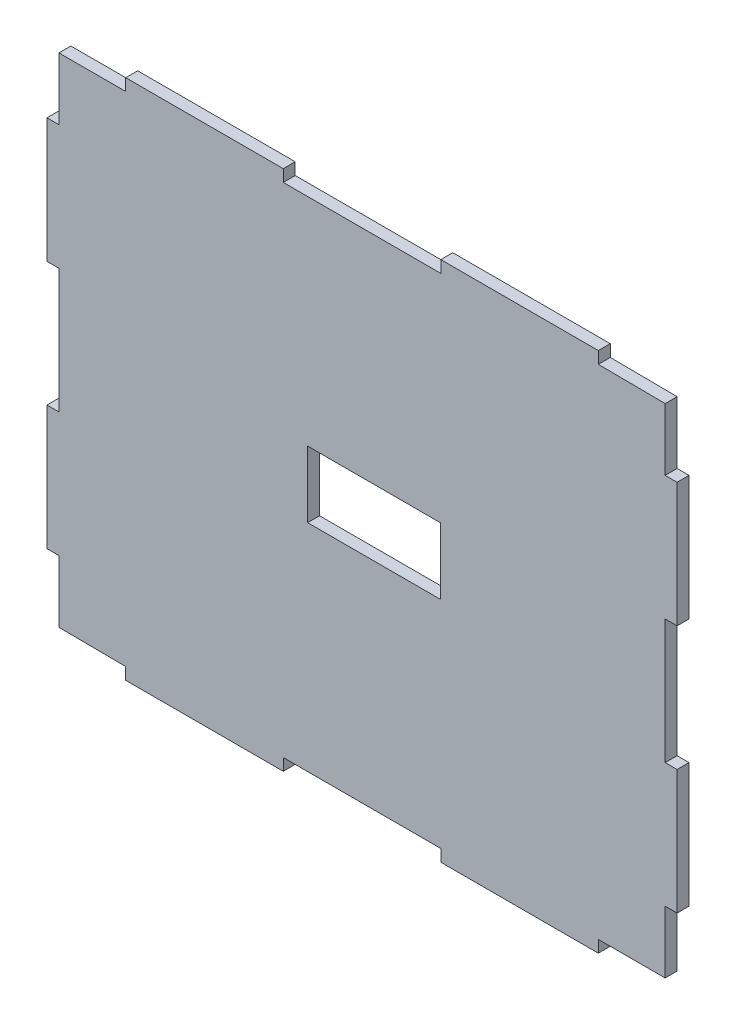
SolidWorks part; units mm, degrees
ref_plane "前视基准面" through (0, 0, 0) normal (0, 0, 1) x (1, 0, 0)
ref_plane "上视基准面" through (0, 0, 0) normal (0, 1, 0) x (1, 0, 0)
ref_plane "右视基准面" through (0, 0, 0) normal (1, 0, 0) x (0, 0, -1)
sketch "草图1" plane through (0, 0, 0) normal (0, 0, 1) x (1, 0, 0)
  line L6 (-95, 75.1729) -> (-74.85, 75.1729)
  line L11 (20.15, 75.1729) -> (-27.35, 75.1729)
  line L14 (87.7993, 75) -> (67.65, 75.1729)
  line L15 (-95, 75.1729) -> (-95, 56.4229)
  line L16 (-98.6, -56.0771) -> (-98.6, -18.5771)
  line L17 (-95, 18.9229) -> (-98.6, 18.9229)
  line L18 (-95, 18.9229) -> (-95, -18.5771)
  line L19 (-74.85, 75.1729) -> (-74.85, 78.7729)
  line L20 (-74.85, 78.7729) -> (-27.35, 78.7729)
  line L21 (-27.35, 78.7729) -> (-27.35, 75.1729)
  line L22 (20.15, 75.1729) -> (20.15, 78.7729)
  line L23 (20.15, 78.7729) -> (67.65, 78.7729)
  line L24 (67.65, 78.7729) -> (67.65, 75.1729)
  line L25 (-95, 56.4229) -> (-98.6, 56.4229)
  line L26 (-98.6, 56.4229) -> (-98.6, 18.9229)
  line L27 (-95, -56.0771) -> (-98.6, -56.0771)
  line L28 (-95, -18.5771) -> (-98.6, -18.5771)
  line L29 (-94.9993, -74.8271) -> (-95, -56.0771)
  line L30 (67.65, -78.6) -> (67.65, -75)
  line L31 (20.15, -78.6) -> (67.65, -78.6)
  line L32 (20.15, -75) -> (20.15, -78.6)
  line L33 (-27.35, -78.6) -> (-27.35, -75)
  line L34 (-74.85, -78.6) -> (-27.35, -78.6)
  line L35 (-74.85, -75) -> (-74.85, -78.6)
  line L37 (20.15, -75) -> (-27.35, -75)
  line L38 (-94.9993, -74.8271) -> (-74.85, -75)
  line L42 (91.3993, 56.25) -> (91.3993, 18.75)
  line L43 (87.7993, 56.25) -> (91.3993, 56.25)
  line L44 (87.7993, 18.75) -> (87.7993, -18.75)
  line L45 (87.7993, 18.75) -> (91.3993, 18.75)
  line L47 (87.7993, 75) -> (87.7993, 56.25)
  line L48 (67.65, -75) -> (87.7993, -75)
  line L49 (87.7993, -18.75) -> (91.3993, -18.75)
  line L50 (91.3993, -18.75) -> (91.3993, -56.25)
  line L51 (91.3993, -56.25) -> (87.7993, -56.25)
  line L53 (87.7993, -56.25) -> (87.7993, -75)
  point P0 (0, 0)
  point P14 (-47.5, 71.4)
  point P17 (47.5, 71.4)
  point P21 (-98.6, 37.6729)
  point P27 (-98.6, -37.5)
  point P36 (47.5, -71.4)
  point P37 (-47.5, -71.4)
  point P46 (98.6, -37.5)
  point P47 (98.6, 37.5)
  dimension "D1" = 47.5
  dimension "D2" = 20.1493
  dimension "D3" = 3.6
  dimension "D4" = 3.6
  dimension "D5" = 20.15
  dimension "D6" = 20.15
  dimension "D7" = 18.75
  dimension "D8" = 37.5
  dimension "D9" = 47.5
  dimension "D10" = 47.5
  dimension "D11" = 18.75
  dimension "D12" = 37.5
  dimension "D13" = 37.5
  dimension "D14" = 37.5
  dimension "D15" = 18.75
  dimension "D16" = 20.15
  dimension "D17" = 47.5
  dimension "D18" = 47.5
  dimension "D19" = 47.5
  dimension "D20" = 37.5
  dimension "D21" = 37.5
  dimension "D22" = 18.75
extrude "凸台-拉伸1" add sketch "草图1" along normal blind 3.6
sketch "草图2" plane through (0, 0, 0) normal (0, 0, -1) x (-1, 0, 0)
  line L0 (-101.2964, 0) -> (127.7142, 0) construction
  line L1 (0, -116.3061) -> (0, 119.7057) construction
  line L3 (-20, -10) -> (20, -10)
  line L4 (-20, -10) -> (-20, 10)
  line L5 (-20, 10) -> (20, 10)
  line L6 (20, -10) -> (20, 10)
  dimension "D1" = 20
  dimension "D2" = 40
  dimension "D3" = 20
  dimension "D4" = 10
extrude "切除-拉伸1" cut sketch "草图2" against normal blind 10
